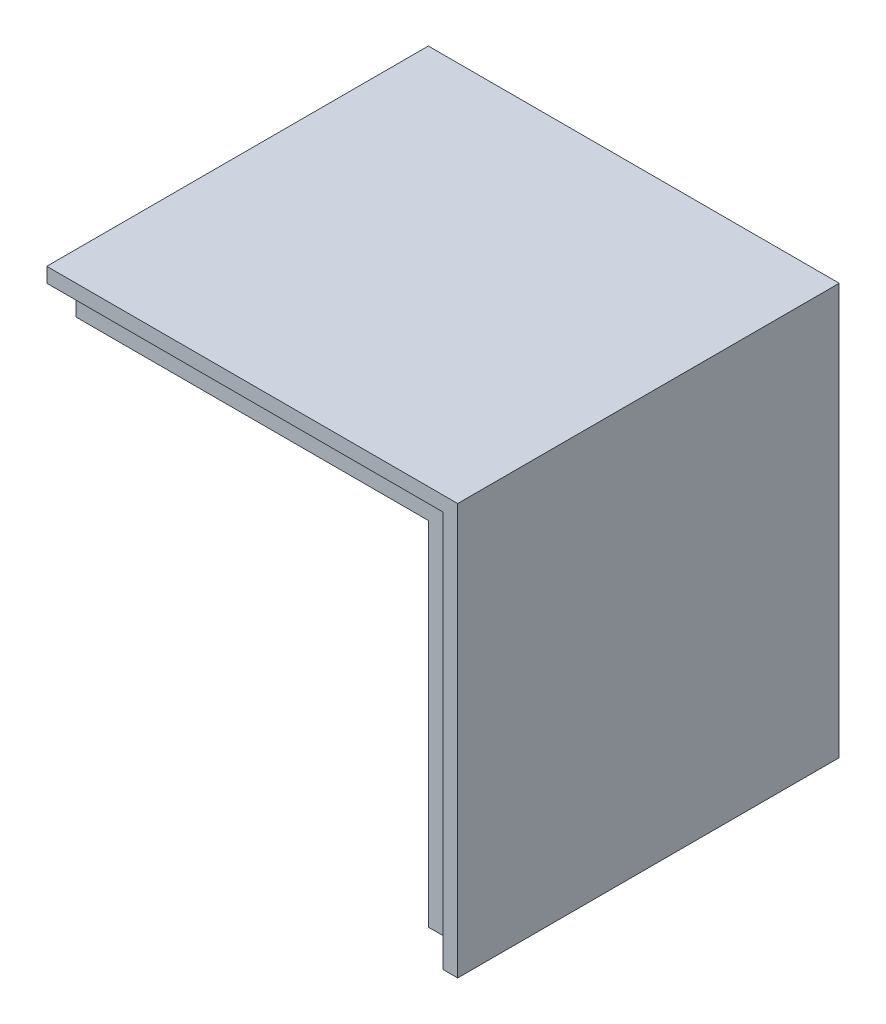
SolidWorks part; units mm, degrees
material "ABS"
ref_plane "Front" through (0, 0, 0) normal (0, 0, 1) x (1, 0, 0)
ref_plane "Top" through (0, 0, 0) normal (0, 1, 0) x (1, 0, 0)
ref_plane "Right" through (0, 0, 0) normal (1, 0, 0) x (0, 0, -1)
sketch "Croquis1" plane through (0, 0, 0) normal (0, 0, 1) x (1, 0, 0)
  line L0 (-70, 72.5) -> (70, 72.5)
  line L1 (70, 72.5) -> (70, -67.5)
  line L2 (70, -67.5) -> (65, -67.5)
  line L3 (65, -67.5) -> (65, 67.5)
  line L4 (65, 67.5) -> (-70, 67.5)
  line L5 (-70, 67.5) -> (-70, 72.5)
  line L6 (71.5, 0) -> (-71.5, 0) construction
  line L7 (0, -71.5) -> (0, 71.5) construction
  point P2 (65, 0)
  point P9 (0, 72.5)
  dimension "D1" = 5
  dimension "D2" = 140
extrude "Saliente-Extruir1" add sketch "Croquis1" along normal mid plane 130
sketch "Croquis2" plane through (0, 0, 0) normal (0, 0, 1) x (1, 0, 0)
  line L0 (-65, 67.5) -> (-65, 57.5)
  line L1 (-70, 67.5) -> (65, 67.5) construction
  line L2 (-65, 57.5) -> (55, 57.5)
  line L3 (55, 57.5) -> (55, -62.5)
  line L4 (55, -62.5) -> (65, -62.5)
  line L5 (65, 67.5) -> (65, -67.5) construction
  line L6 (65, -62.5) -> (65, 67.5)
  line L7 (65, 67.5) -> (-65, 67.5)
  dimension "D1" = 10
  dimension "D2" = 130
extrude "Saliente-Extruir2" add sketch "Croquis2" along normal mid plane 120
